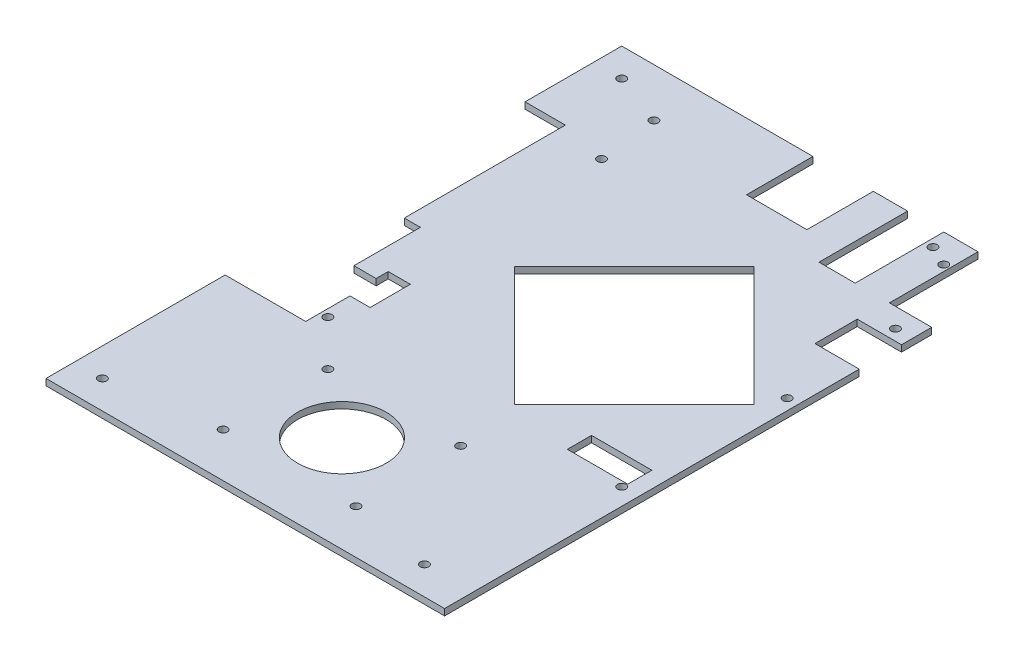
SolidWorks part; units mm, degrees
ref_plane "前视基准面" through (0, 0, 0) normal (0, 0, 1) x (1, 0, 0)
ref_plane "上视基准面" through (0, 0, 0) normal (0, 1, 0) x (1, 0, 0)
ref_plane "右视基准面" through (0, 0, 0) normal (1, 0, 0) x (0, 0, -1)
sketch "草图1" plane through (0, 0, 0) normal (0, 1, 0) x (1, 0, 0)
  line L0 (63.8015, -31) -> (34.103, -60.6985)
  line L1 (0, 0) -> (99, 0)
  line L2 (0, 0) -> (0, -99)
  line L3 (0, -99) -> (99, -99)
  line L4 (99, 0) -> (99, -99)
  line L5 (21.8, -26.8) -> (94.8, -26.8) construction
  line L6 (21.8, -26.8) -> (21.8, -94.8) construction
  line L7 (21.8, -94.8) -> (94.8, -94.8) construction
  line L8 (94.8, -26.8) -> (94.8, -94.8) construction
  line L9 (0, -99) -> (99, -99)
  line L10 (0, -99) -> (0, -143)
  line L11 (0, -143) -> (99, -143)
  line L12 (99, -99) -> (99, -143)
  line L13 (5, -5) -> (89, -5) construction
  line L14 (5, -5) -> (5, -138) construction
  line L15 (5, -138) -> (89, -138) construction
  line L16 (89, -5) -> (89, -138) construction
  line L17 (7, -7) -> (87, -7) construction
  line L18 (7, -7) -> (7, -136) construction
  line L19 (7, -136) -> (87, -136) construction
  line L20 (87, -7) -> (87, -136) construction
  line L21 (31, -104) -> (68, -104) construction
  line L22 (31, -104) -> (31, -134) construction
  line L23 (31, -134) -> (68, -134) construction
  line L24 (68, -104) -> (68, -134) construction
  line L25 (33, -106) -> (66, -106) construction
  line L26 (33, -106) -> (33, -132) construction
  line L27 (33, -132) -> (66, -132) construction
  line L28 (66, -106) -> (66, -132) construction
  line L29 (0, -24) -> (10, -24)
  line L30 (0, -24) -> (0, -64)
  line L31 (0, -64) -> (10, -64)
  line L32 (10, -24) -> (10, -64)
  line L33 (0, -64) -> (14, -64)
  line L34 (0, -64) -> (0, -80.5)
  line L35 (0, -80.5) -> (14, -80.5)
  line L36 (14, -64) -> (14, -80.5)
  line L37 (0, -80.5) -> (20, -80.5)
  line L38 (0, -80.5) -> (0, -98.5)
  line L39 (0, -98.5) -> (20, -98.5)
  line L40 (20, -80.5) -> (20, -98.5)
  line L41 (99, 0) -> (88.5, 0)
  line L42 (99, 0) -> (99, -22)
  line L43 (99, -22) -> (88.5, -22)
  line L44 (88.5, 0) -> (88.5, -22)
  line L45 (80, 0) -> (71, 0)
  line L46 (80, 0) -> (80, -22)
  line L47 (80, -22) -> (71, -22)
  line L48 (71, 0) -> (71, -22)
  line L49 (62.5, 0) -> (47.5, 0)
  line L50 (62.5, 0) -> (62.5, -16.5)
  line L51 (62.5, -16.5) -> (47.5, -16.5)
  line L52 (47.5, 0) -> (47.5, -16.5)
  line L53 (99, -29.5) -> (88, -29.5)
  line L54 (99, -29.5) -> (99, -40)
  line L55 (99, -40) -> (88, -40)
  line L56 (88, -29.5) -> (88, -40)
  line L57 (34.103, -31) -> (93.5, -31) construction
  line L58 (34.103, -31) -> (34.103, -90.397) construction
  line L59 (34.103, -90.397) -> (93.5, -90.397) construction
  line L60 (93.5, -31) -> (93.5, -90.397) construction
  line L61 (34.103, -60.6985) -> (63.8015, -90.397)
  line L62 (63.8015, -90.397) -> (93.5, -60.6985)
  line L63 (93.5, -60.6985) -> (63.8015, -31)
  line L65 (19.5, -77.5) -> (25, -77.5)
  line L66 (19.5, -77.5) -> (19.5, -87.5)
  line L67 (19.5, -87.5) -> (25, -87.5)
  line L68 (25, -77.5) -> (25, -87.5)
  line L69 (80, -87.5) -> (95, -87.5)
  line L70 (80, -87.5) -> (80, -93.5)
  line L71 (80, -93.5) -> (95, -93.5)
  line L72 (95, -87.5) -> (95, -93.5)
  circle A0 centre (21.8, -26.8) radius 1.05
  circle A1 centre (94.8, -26.8) radius 1.05
  circle A2 centre (21.8, -94.8) radius 1.05
  circle A3 centre (94.8, -94.8) radius 1.05
  circle A4 centre (8.7, -65.7) radius 1.05
  circle A5 centre (81.9, -4.6) radius 1.05
  circle A6 centre (96.3, -55.2) radius 1.05
  circle A7 centre (20, -12) radius 1.05
  circle A8 centre (71.4, -77.5) radius 1.05
  circle A9 centre (7, -7) radius 1.05
  circle A10 centre (87, -7) radius 1.05
  circle A11 centre (7, -136) radius 1.05
  circle A12 centre (87, -136) radius 1.05
  circle A14 centre (33, -106) radius 1.05
  circle A15 centre (66, -106) radius 1.05
  circle A16 centre (33, -132) radius 1.05
  circle A17 centre (66, -132) radius 1.05
  circle A18 centre (49.5, -119) radius 11
  dimension "D7" = 2.1
  dimension "D8" = 2.1
  dimension "D9" = 2.1
  dimension "D10" = 2.1
  dimension "D21" = 2.1
  dimension "D22" = 2.1
  dimension "D23" = 2.1
  dimension "D24" = 2.1
  dimension "D25" = 2.1
  dimension "D33" = 2.1
  dimension "D34" = 2.1
  dimension "D35" = 2.1
  dimension "D36" = 2.1
  dimension "D39" = 24
  dimension "D48" = 2.1
  dimension "D49" = 2.1
  dimension "D50" = 2.1
  dimension "D51" = 2.1
  dimension "D72" = 22
  dimension "D1" = 99
  dimension "D2" = 99
  dimension "D3" = 21.8
  dimension "D4" = 4.2
  dimension "D5" = 68
  dimension "D6" = 73
  dimension "D11" = 8.7
  dimension "D12" = 33.3
  dimension "D13" = 81.9
  dimension "D14" = 94.4
  dimension "D15" = 96.3
  dimension "D16" = 43.8
  dimension "D17" = 20
  dimension "D18" = 87
  dimension "D19" = 71.4
  dimension "D20" = 21.5
  dimension "D26" = 143
  dimension "D27" = 2
  dimension "D28" = 2
  dimension "D29" = 2
  dimension "D30" = 2
  dimension "D31" = 84
  dimension "D32" = 133
  dimension "D37" = 5
  dimension "D38" = 5
  dimension "D40" = 40
  dimension "D41" = 16.5
  dimension "D42" = 2
  dimension "D43" = 2
  dimension "D44" = 2
  dimension "D45" = 2
  dimension "D46" = 37
  dimension "D47" = 30
  dimension "D52" = 5
  dimension "D53" = 31
  dimension "D54" = 18
  dimension "D55" = 10
  dimension "D56" = 14
  dimension "D57" = 20
  dimension "D58" = 0
  dimension "D59" = 8.5
  dimension "D60" = 9
  dimension "D61" = 8.5
  dimension "D62" = 10.5
  dimension "D63" = 15
  dimension "D64" = 22
  dimension "D65" = 16.5
  dimension "D66" = 11
  dimension "D67" = 10.5
  dimension "D68" = 29.5
  dimension "D69" = 42
  dimension "D70" = 31
  dimension "D71" = 5.5
  dimension "D73" = 49.5
  dimension "D74" = 24
  dimension "D75" = 19.5
  dimension "D76" = 5.5
  dimension "D77" = 11.5
  dimension "D78" = 10
  dimension "D79" = 15
  dimension "D80" = 4
  dimension "D81" = 5.5
  dimension "D82" = 6
extrude "凸台-拉伸1" add sketch "草图1" along normal blind 1.6 contours L4 L1 L2 L3 A10 A9 A8 A7 A6 A5 A4 A3 A2 A1 A0 | L12 L3 L10 L11 A12 A11
